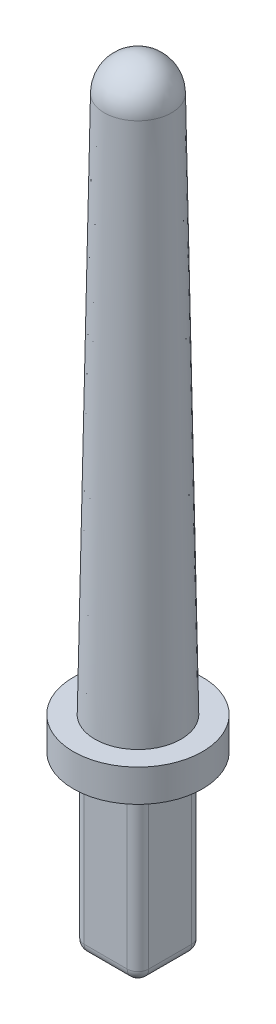
SolidWorks part; units mm, degrees
material "ABS"
ref_plane "Front" through (0, 0, 0) normal (0, 0, 1) x (1, 0, 0)
ref_plane "Top" through (0, 0, 0) normal (0, 1, 0) x (1, 0, 0)
ref_plane "Right" through (0, 0, 0) normal (1, 0, 0) x (0, 0, -1)
sketch "Sketch10" plane through (0, 0, 0) normal (0, 1, 0) x (1, 0, 0)
  line L1 (-1.5, -1.5) -> (1.5, -1.5)
  line L2 (-1.5, -1.5) -> (-1.5, 1.5)
  line L3 (-1.5, 1.5) -> (1.5, 1.5)
  line L4 (1.5, -1.5) -> (1.5, 1.5)
  line L5 (-1.5, -1.5) -> (1.5, 1.5) construction
  line L6 (-1.5, 1.5) -> (1.5, -1.5) construction
  point P0 (0, 0)
  dimension "D1" = 3
extrude "Handle" add sketch "Sketch10" along normal blind 8
sketch "Sketch13" plane through (0, 8, 0) normal (0, 1, 0) x (1, 0, 0)
  circle A0 centre (0, 0) radius 3
  dimension "D1" = 6
extrude "Guard" add sketch "Sketch13" along normal blind 1.5
sketch "Sketch11" plane through (0, 9.5, 0) normal (0, 1, 0) x (1, 0, 0)
  circle A0 centre (0, 0) radius 2
  dimension "D1" = 4
extrude "Blade" add sketch "Sketch11" along normal blind 25 draft 1
sketch "Sketch12" plane through (0, 34.5, 0) normal (0, 1, 0) x (1, 0, 0)
  line L0 (0, 0) -> (0, 4.9804) construction
  line L1 (0, -1.5636) -> (0, 1.5636)
  arc A0 (0, -1.5636) -> (0, 1.5636) centre (0, 0) cw
  circle A1 centre (0, 0) radius 1.5636 construction
revolve "Blade tip" add sketch "Sketch12" angle 180 about L0
fillet "Easy hand insert" radius 0.5 8 edges at (0, 0, -1.5) (-1.5, 0, 0) (0, 0, 1.5) (1.5, 0, 0) (-1.5, 4, -1.5) (1.5, 4, -1.5) (-1.5, 4, 1.5) (1.5, 4, 1.5)
fillet "Smoothing edges" [suppressed] radius 0.1
scale "Scale1" scale about centroid uniform scaling yes scale factor 2
